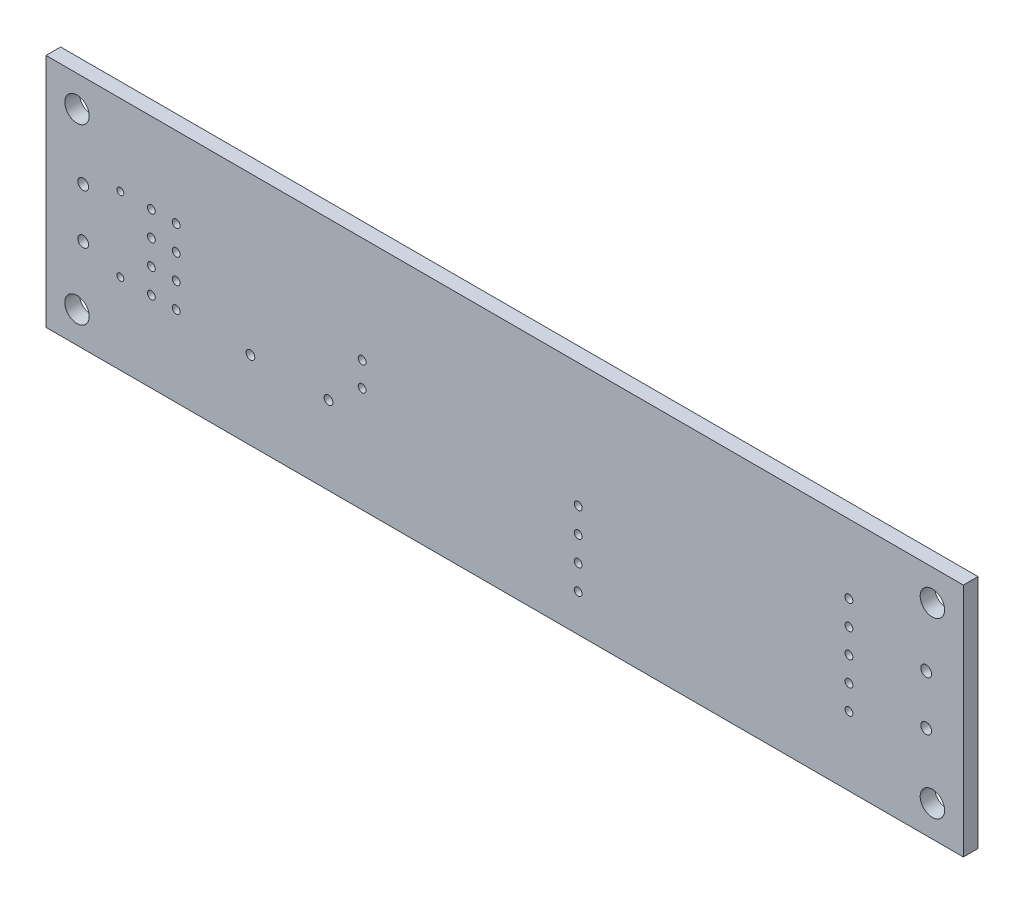
SolidWorks part; units mm, degrees
ref_plane "Спереди" through (0, 0, 0) normal (0, 0, 1) x (1, 0, 0)
ref_plane "Сверху" through (0, 0, 0) normal (0, 1, 0) x (1, 0, 0)
ref_plane "Справа" through (0, 0, 0) normal (1, 0, 0) x (0, 0, -1)
ref_plane "Плоскость4" through (0, 0, -0.3454) normal (0, 0, -1) x (-1, 0, 0)
sketch "Эскиз1" plane through (0, 0, -0.3454) normal (0, 0, -1) x (-1, 0, 0)
  line L0 (-72.39, 95.885) -> (-166.37, 95.885)
  line L1 (-166.37, 95.885) -> (-166.37, 71.755)
  line L2 (-166.37, 71.755) -> (-72.39, 71.755)
  line L3 (-72.39, 71.755) -> (-72.39, 95.885)
  circle A0 centre (-163.195, 92.71) radius 1.25
  circle A1 centre (-154.65, 88.82) radius 0.4
  circle A2 centre (-162.56, 86.36) radius 0.55
  circle A3 centre (-154.65, 86.32) radius 0.4
  circle A4 centre (-154.65, 83.82) radius 0.4
  circle A5 centre (-104.775, 85.05) radius 0.4
  circle A6 centre (-126.9075, 83.185) radius 0.4
  circle A7 centre (-104.775, 82.55) radius 0.4
  circle A8 centre (-162.56, 81.28) radius 0.55
  circle A9 centre (-154.65, 81.32) radius 0.4
  circle A10 centre (-163.195, 74.93) radius 1.25
  circle A11 centre (-154.65, 78.82) radius 0.4
  circle A12 centre (-126.9075, 80.645) radius 0.4
  circle A13 centre (-101.33, 79.78) radius 0.45
  circle A14 centre (-126.9075, 75.565) radius 0.4
  circle A15 centre (-126.9075, 78.105) radius 0.4
  circle A16 centre (-85.725, 87.63) radius 0.4
  circle A17 centre (-83.185, 87.63) radius 0.4
  circle A18 centre (-85.725, 82.55) radius 0.4
  circle A19 centre (-85.725, 85.09) radius 0.4
  circle A20 centre (-80.01, 87.63) radius 0.35
  circle A21 centre (-75.565, 92.71) radius 1.25
  circle A22 centre (-83.185, 85.09) radius 0.4
  circle A23 centre (-76.2, 86.36) radius 0.55
  circle A24 centre (-85.725, 80.01) radius 0.4
  circle A25 centre (-83.185, 82.55) radius 0.4
  circle A26 centre (-93.33, 79.78) radius 0.45
  circle A27 centre (-83.185, 80.01) radius 0.4
  circle A28 centre (-80.01, 80.03) radius 0.35
  circle A29 centre (-76.2, 81.28) radius 0.55
  circle A30 centre (-75.565, 74.93) radius 1.25
extrude "Бобышка-Вытянуть1" add sketch "Эскиз1" against normal blind 1.5
